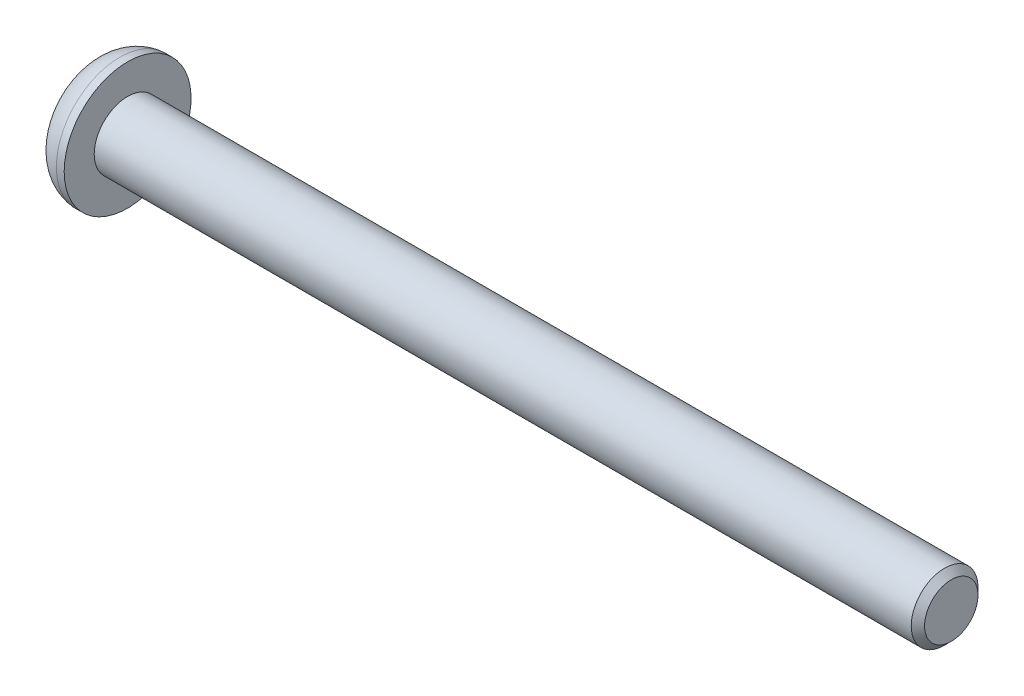
SolidWorks part; units mm, degrees
ref_plane "Ön Düzlem" through (0, 0, 0) normal (0, 0, 1) x (1, 0, 0)
ref_plane "Üst Düzlem" through (0, 0, 0) normal (0, 1, 0) x (1, 0, 0)
ref_plane "Sağ Düzlem" through (0, 0, 0) normal (1, 0, 0) x (0, 0, -1)
sketch "Çizim1" plane through (0, 0, 0) normal (0, 0, 1) x (1, 0, 0)
  line L0 (-8.7487, 0) -> (10.0219, 0) construction
  line L1 (-17.8952, 0) -> (-17.8952, 1.425)
  line L2 (-16.5952, 2.85) -> (-16.2452, 2.85)
  line L3 (-16.2452, 2.85) -> (-16.2452, 1.5)
  line L4 (-16.2452, 1.5) -> (20.4548, 1.5)
  line L5 (20.4548, 1.5) -> (20.7548, 1.2)
  line L6 (20.7548, 1.2) -> (20.7548, 0)
  line L7 (-17.8952, 0) -> (20.7548, 0)
  arc A0 (-17.8952, 1.425) -> (-16.5952, 2.85) centre (-16.4641, 1.425) cw
  dimension "D1" = 1.425
  dimension "D5" = 0.35
  dimension "D2" = 2.85
  dimension "D3" = 37
  dimension "D4" = 1.5
  dimension "D6" = 135
  dimension "D7" = 0.3
  dimension "D8" = 1.65
revolve "Döndür1" add sketch "Çizim1" angle 360 about L0
sketch "Çizim2" plane through (-17.8952, 0, 0) normal (-1, 0, 0) x (0, 0, 1)
  line L1 (0, 1.1547) -> (-1, 0.5774)
  line L2 (-1, 0.5774) -> (-1, -0.5774)
  line L3 (-1, -0.5774) -> (0, -1.1547)
  line L4 (0, -1.1547) -> (1, -0.5774)
  line L5 (1, -0.5774) -> (1, 0.5774)
  line L6 (1, 0.5774) -> (0, 1.1547)
  circle A0 centre (0, 0) radius 1 construction
  dimension "D1" = 2
extrude "Kes-Ekstrüzyon1" cut sketch "Çizim2" against normal blind 1
